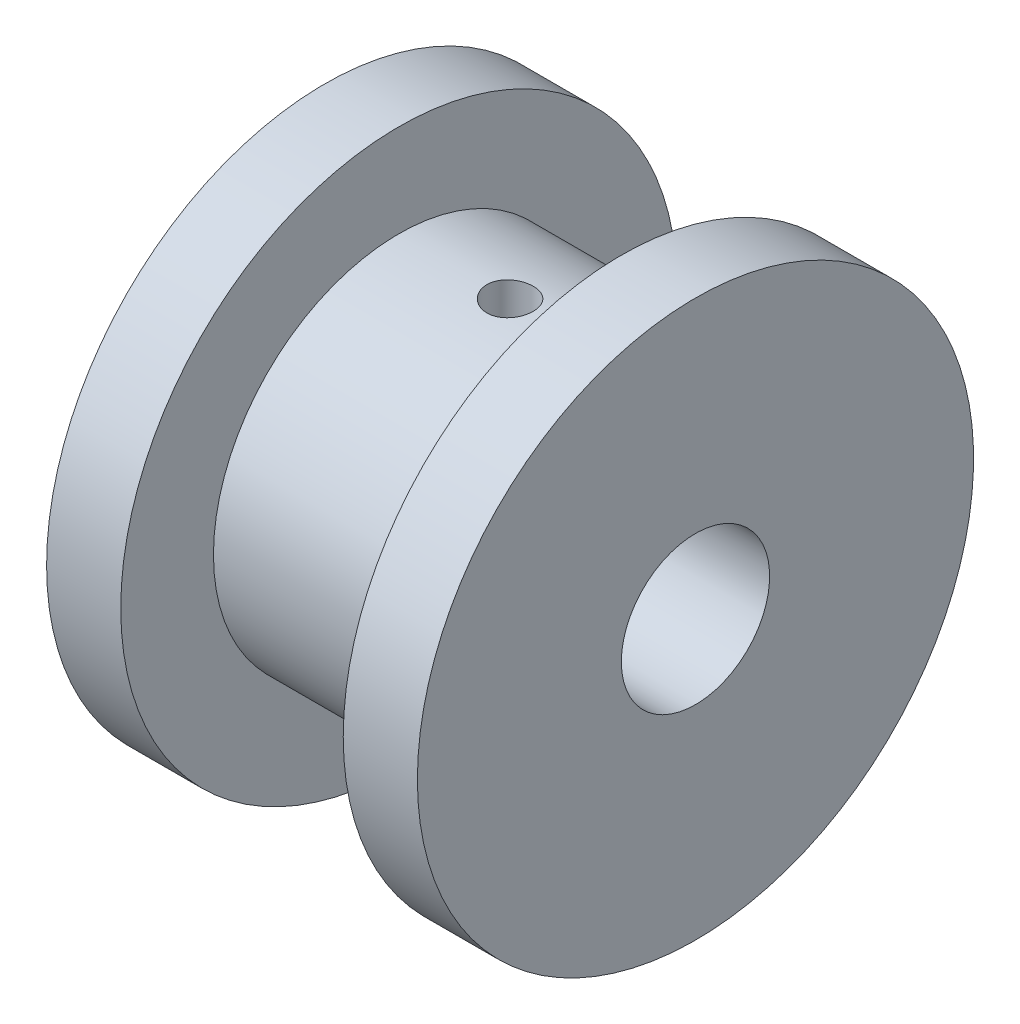
SolidWorks part; units mm, degrees
ref_plane "Front Plane" through (0, 0, 0) normal (0, 0, 1) x (1, 0, 0)
ref_plane "Top Plane" through (0, 0, 0) normal (0, 1, 0) x (1, 0, 0)
ref_plane "Right Plane" through (0, 0, 0) normal (1, 0, 0) x (0, 0, -1)
sketch "Sketch1" plane through (0, 0, 0) normal (0, 1, 0) x (1, 0, 0)
  line L0 (0, 0) -> (20, 0) construction
  line L1 (0, 4) -> (0, 0) construction
  line L2 (0, 4) -> (20, 4)
  line L3 (0, 4) -> (0, 15)
  line L5 (20, 4) -> (20, 15)
  line L6 (20, 4) -> (20, 0) construction
  line L7 (0, 15) -> (4, 15)
  line L8 (4, 15) -> (4, 10)
  line L9 (4, 10) -> (16, 10)
  line L10 (16, 10) -> (16, 15)
  line L11 (16, 15) -> (20, 15)
  dimension "D1" = 4
  dimension "D2" = 4
  dimension "D3" = 20
  dimension "D4" = 6
  dimension "D5" = 15
revolve "Revolve1" add sketch "Sketch1" angle 360 about L0
hole_wizard "M3 Tapped Hole1" positions "3DSketch1" profile "Sketch2" tap size "M3" standard "DIN"
sketch3d "3DSketch1"
  line L0 (4, 10, 0) -> (16, 10, 0) construction
  circle A0 centre (4, 0, 0) radius 10 construction
  circle A1 centre (16, 0, 0) radius 10 construction
  point P0 (10, 10, 0)
  point P7 (-6, 0, 0)
  point P10 (6, 0, 0)
  point P12 (0, 0, 0)
sketch "Sketch2" plane through (10, 10, 0) normal (1, 0, 0) x (0, 0, 1)
  line L0 (0, 0) -> (0, 6)
  line L1 (0, 6) -> (1.25, 6)
  line L2 (1.25, 6) -> (1.25, 0)
  line L5 (1.25, 0) -> (0, 0)
  line L11 (0, -6.35) -> (0, 107.95) construction
  dimension "Thru Tap Drill Dia." = 2.5
  dimension "Thru Tap Drill Depth" = 6
cosmetic thread "Hole Thread1" parameters "D2"=3
